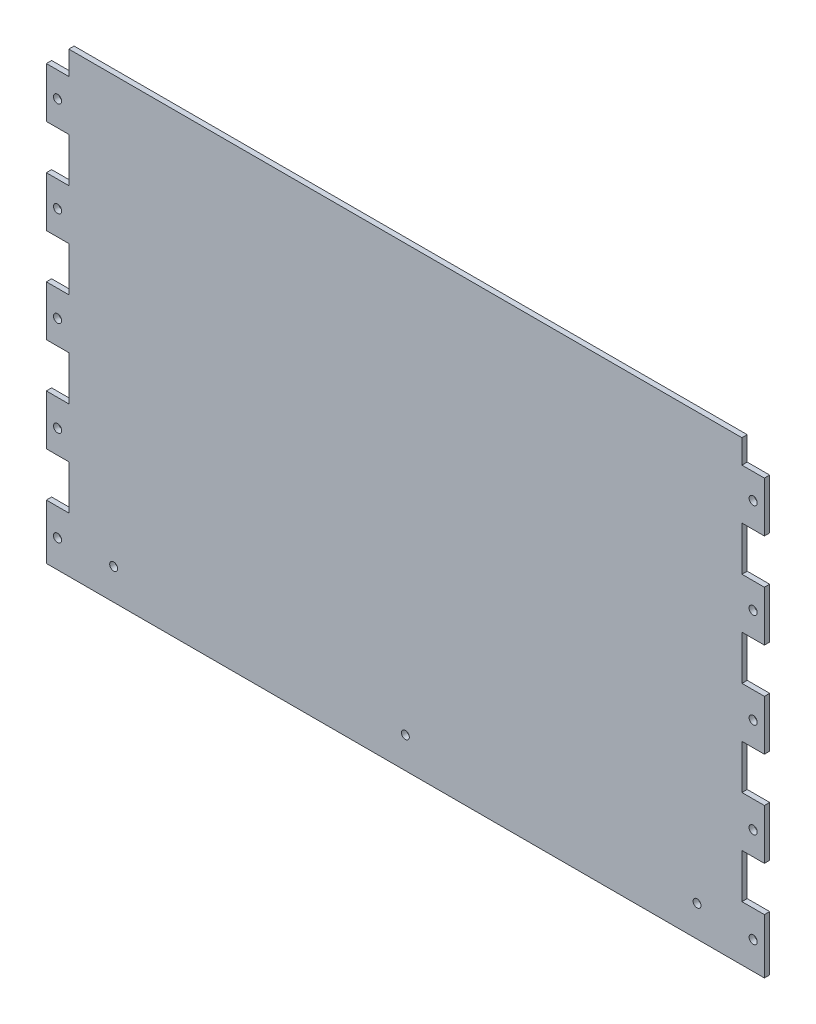
SolidWorks part; units mm, degrees
ref_plane "Front Plane" through (0, 0, 0) normal (0, 0, 1) x (1, 0, 0)
ref_plane "Top Plane" through (0, 0, 0) normal (0, 1, 0) x (1, 0, 0)
ref_plane "Right Plane" through (0, 0, 0) normal (1, 0, 0) x (0, 0, -1)
sketch "Sketch1" plane through (0, 0, 0) normal (0, 0, 1) x (1, 0, 0)
  line L0 (0, 20.8) -> (8.5, 20.8)
  line L1 (0, 0) -> (272, 0)
  line L2 (0, 0) -> (0, 20.8)
  line L3 (8.5, 173) -> (263.5, 173)
  line L4 (272, 0) -> (272, 20.8)
  line L5 (8.5, 20.8) -> (8.5, 37.6)
  line L6 (8.5, 37.6) -> (0, 37.6)
  line L7 (0, 56.6) -> (8.5, 56.6)
  line L8 (8.5, 56.6) -> (8.5, 73.4)
  line L9 (8.5, 73.4) -> (0, 73.4)
  line L10 (0, 92.4) -> (8.5, 92.4)
  line L11 (8.5, 92.4) -> (8.5, 109.2)
  line L12 (8.5, 109.2) -> (0, 109.2)
  line L13 (0, 128.2) -> (8.5, 128.2)
  line L14 (8.5, 128.2) -> (8.5, 145)
  line L15 (8.5, 145) -> (0, 145)
  line L16 (0, 164) -> (8.5, 164)
  line L17 (8.5, 164) -> (8.5, 173)
  line L18 (0, 145) -> (0, 164)
  line L19 (0, 109.2) -> (0, 128.2)
  line L20 (0, 73.4) -> (0, 92.4)
  line L21 (0, 37.6) -> (0, 56.6)
  line L22 (136, 0) -> (136, 173) construction
  line L23 (263.5, 128.2) -> (263.5, 145)
  line L24 (263.5, 92.4) -> (263.5, 109.2)
  line L25 (263.5, 56.6) -> (263.5, 73.4)
  line L26 (263.5, 20.8) -> (263.5, 37.6)
  line L27 (272, 20.8) -> (263.5, 20.8)
  line L28 (263.5, 37.6) -> (272, 37.6)
  line L29 (272, 56.6) -> (263.5, 56.6)
  line L30 (263.5, 73.4) -> (272, 73.4)
  line L31 (272, 92.4) -> (263.5, 92.4)
  line L32 (263.5, 109.2) -> (272, 109.2)
  line L33 (272, 128.2) -> (263.5, 128.2)
  line L34 (263.5, 145) -> (272, 145)
  line L35 (272, 164) -> (263.5, 164)
  line L36 (263.5, 164) -> (263.5, 173)
  line L37 (272, 145) -> (272, 164)
  line L38 (272, 109.2) -> (272, 128.2)
  line L39 (272, 73.4) -> (272, 92.4)
  line L40 (272, 37.6) -> (272, 56.6)
  circle A0 centre (4.25, 154.5) radius 1.55
  circle A1 centre (4.25, 118.5) radius 1.55
  circle A2 centre (4.25, 82.5) radius 1.55
  circle A3 centre (4.25, 46.5) radius 1.55
  circle A4 centre (4.25, 10.5) radius 1.55
  circle A5 centre (267.75, 10.5) radius 1.55
  circle A6 centre (267.75, 46.5) radius 1.55
  circle A7 centre (267.75, 82.5) radius 1.55
  circle A8 centre (267.75, 118.5) radius 1.55
  circle A9 centre (267.75, 154.5) radius 1.55
  circle A10 centre (25.5, 11.75) radius 1.5
  circle A11 centre (136, 11.75) radius 1.5
  circle A12 centre (246.5, 11.75) radius 1.5
  point P11 (4.25, 56.6)
  point P28 (0, 154.5)
  dimension "D10" = 4.25
  dimension "D11" = 3.1
  dimension "D13" = 3
  dimension "D1" = 272
  dimension "D2" = 173
  dimension "D3" = 8.5
  dimension "D4" = 20.8
  dimension "D5" = 16.8
  dimension "D6" = 19
  dimension "D7" = 19
  dimension "D8" = 19
  dimension "D9" = 19
  dimension "D14" = 17
  dimension "D15" = 11.75
  dimension "D17" = 21.25
  dimension "D12" = 5
  dimension "D16" = 3
extrude "Boss-Extrude1" add sketch "Sketch1" along normal blind 2
